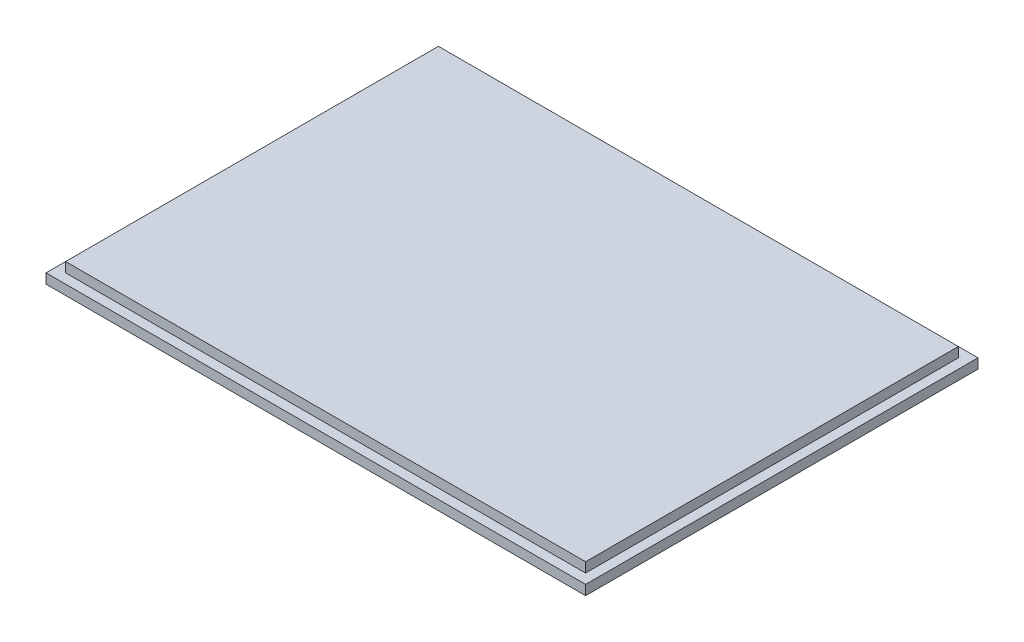
SolidWorks part; units mm, degrees
ref_plane "Front Plane" through (0, 0, 0) normal (0, 0, 1) x (1, 0, 0)
ref_plane "Top Plane" through (0, 0, 0) normal (0, 1, 0) x (1, 0, 0)
ref_plane "Right Plane" through (0, 0, 0) normal (1, 0, 0) x (0, 0, -1)
sketch "Sketch1" plane through (0, 0, 0) normal (0, 1, 0) x (1, 0, 0)
  line L1 (-110, -80) -> (110, -80)
  line L2 (-110, -80) -> (-110, 80)
  line L3 (-110, 80) -> (110, 80)
  line L4 (110, -80) -> (110, 80)
  line L5 (-110, -80) -> (110, 80) construction
  line L6 (-110, 80) -> (110, -80) construction
  point P0 (0, 0)
  dimension "D1" = 220
  dimension "D2" = 160
extrude "Boss-Extrude1" add sketch "Sketch1" along normal blind 8
sketch "Sketch2" plane through (0, 8, 0) normal (0, 1, 0) x (1, 0, 0)
  line L0 (110, 80) -> (-110, 80) construction
  line L1 (-106, -76) -> (106, -76)
  line L2 (-106, -76) -> (-106, 76)
  line L3 (-106, 76) -> (106, 76)
  line L4 (106, -76) -> (106, 76)
  line L5 (-106, -76) -> (106, 76) construction
  line L6 (-106, 76) -> (106, -76) construction
  line L7 (-110, 80) -> (-110, -80) construction
  line L9 (-110, -80) -> (110, -80)
  line L10 (-110, -80) -> (-110, 80)
  line L11 (-110, 80) -> (110, 80)
  line L12 (110, -80) -> (110, 80)
  line L13 (-110, -80) -> (110, 80) construction
  line L14 (-110, 80) -> (110, -80) construction
  point P0 (0, 0)
  point P10 (0, 0)
  dimension "D1" = 4
  dimension "D2" = 4
extrude "Cut-Extrude1" cut sketch "Sketch2" against normal blind 4
